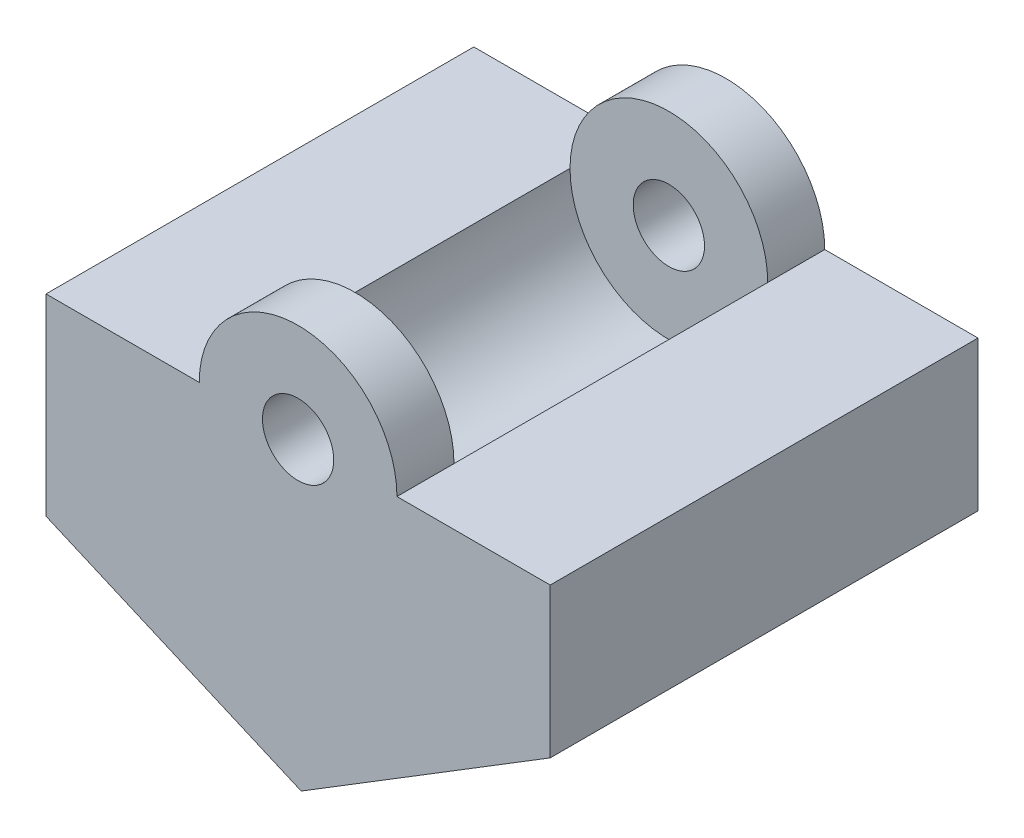
SolidWorks part; units mm, degrees
ref_plane "Front Plane" through (0, 0, 0) normal (0, 0, 1) x (1, 0, 0)
ref_plane "Top Plane" through (0, 0, 0) normal (0, 1, 0) x (1, 0, 0)
ref_plane "Right Plane" through (0, 0, 0) normal (1, 0, 0) x (0, 0, -1)
sketch "Sketch1" plane through (0, 0, 0) normal (0, 0, 1) x (1, 0, 0)
  line L0 (0, 0) -> (-35.7936, 15.4861)
  line L1 (-35.7936, 15.4861) -> (-35.7936, 42.4861)
  line L2 (-35.7936, 42.4861) -> (-14.3013, 42.4861)
  line L3 (34.9192, 42.4861) -> (34.9192, 21.4861)
  line L4 (34.9192, 21.4861) -> (0, 0)
  line L5 (13.4269, 42.4861) -> (34.9192, 42.4861)
  line L6 (-14.3013, 42.4861) -> (13.4269, 42.4861) construction
  arc A0 (13.4269, 42.4861) -> (-14.3013, 42.4861) centre (-0.4372, 42.4861) ccw
  dimension "D1" = 21.4923
  dimension "D2" = 21
  dimension "D3" = 41
  dimension "D4" = 39
  dimension "D5" = 27
  dimension "D6" = 125
extrude "Boss-Extrude1" add sketch "Sketch1" along normal blind 60
sketch "Sketch3" plane through (0, 0, 60) normal (0, 0, 1) x (1, 0, 0)
  line L0 (-14.3013, 42.4861) -> (13.4269, 42.4861) construction
  circle A0 centre (-0.4372, 42.4861) radius 13.8641
extrude "Cut-Extrude1" cut sketch "Sketch3" against normal offset from surface (44 mm away) 8 from offset 8 up to face at (-0.3748, 31.5401, 0) offset against normal yes
sketch "Sketch4" plane through (0, 0, 60) normal (0, 0, 1) x (1, 0, 0)
  line L0 (-14.3013, 42.4861) -> (13.4269, 42.4861) construction
  circle A0 centre (-0.4372, 42.4861) radius 5
  dimension "D1" = 10
extrude "Cut-Extrude2" cut sketch "Sketch4" against normal through all
sketch "Sketch5" plane through (0, 0, 0) normal (-0.3971, -0.9178, 0) x (0.9178, -0.3971, 0)
  circle A0 centre (-29, 51) radius 4.5
  circle A1 centre (-29, 9) radius 4.5
  dimension "D1" = 9
  dimension "D2" = 9
extrude "Cut-Extrude3" cut sketch "Sketch5" against normal blind 15
